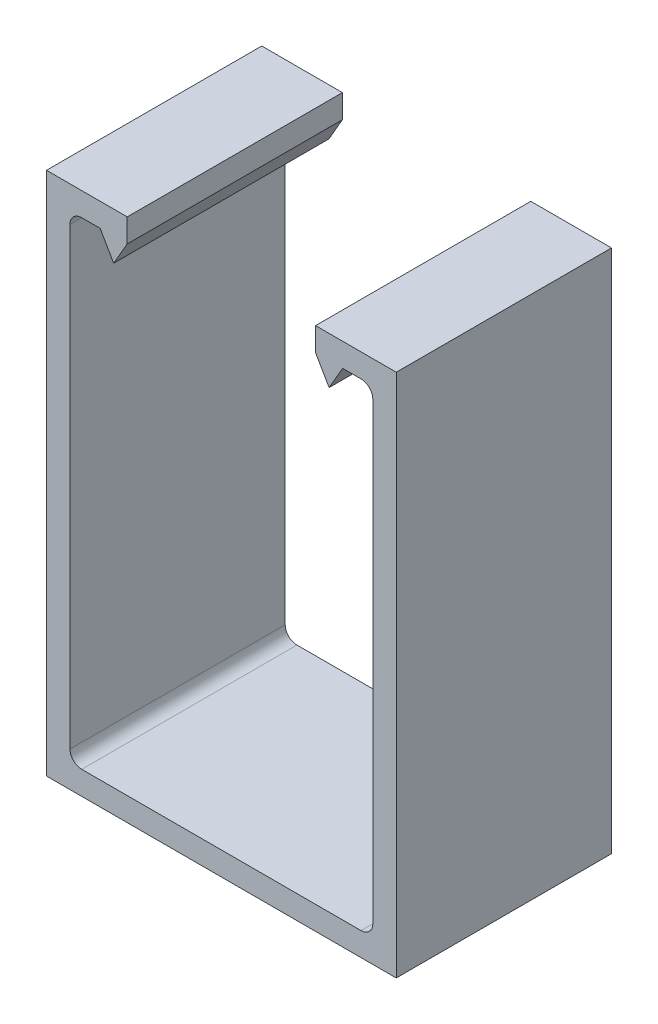
SolidWorks part; units mm, degrees
ref_plane "Plane1" through (0, 0, 0) normal (0, 0, 1) x (1, 0, 0)
ref_plane "Plane2" through (0, 0, 0) normal (0, 1, 0) x (1, 0, 0)
ref_plane "Plane3" through (0, 0, 0) normal (1, 0, 0) x (0, 0, -1)
sketch "Sketch1" plane through (0, 0, 0) normal (0, 0, 1) x (1, 0, 0)
  line L0 (-11.1125, 30.9562) -> (-20.6375, 30.9562)
  line L1 (-20.6375, 30.9562) -> (-20.6375, -30.9562)
  line L2 (-20.6375, -30.9562) -> (20.6375, -30.9562)
  line L3 (20.6375, -30.9562) -> (20.6375, 30.9563)
  line L4 (20.6375, 30.9563) -> (11.1125, 30.9563)
  line L5 (16.4846, 28.1877) -> (14.3094, 28.1877)
  line L6 (17.8689, -26.8033) -> (17.8689, 26.8034)
  line L7 (-16.4846, -28.1876) -> (16.4846, -28.1876)
  line L8 (-17.8689, 26.8033) -> (-17.8689, -26.8033)
  line L9 (-14.3094, 28.1876) -> (-16.4846, 28.1876)
  line L10 (14.3094, 28.1877) -> (12.711, 25.4191)
  line L11 (12.711, 25.4191) -> (11.1125, 28.1877)
  line L12 (11.1125, 28.1877) -> (11.1125, 30.9563)
  line L13 (-14.3094, 28.1876) -> (-12.711, 25.4191)
  line L14 (-12.711, 25.4191) -> (-11.1125, 28.1876)
  line L15 (-11.1125, 28.1876) -> (-11.1125, 30.9562)
  arc A0 (-17.8689, -26.8033) -> (-16.4846, -28.1876) centre (-16.4846, -26.8033) ccw
  arc A1 (-16.4846, 28.1876) -> (-17.8689, 26.8033) centre (-16.4846, 26.8033) ccw
  arc A2 (17.8689, 26.8034) -> (16.4846, 28.1877) centre (16.4846, 26.8034) ccw
  arc A3 (16.4846, -28.1876) -> (17.8689, -26.8033) centre (16.4846, -26.8033) ccw
  dimension "D5" = 1.3843
  dimension "Width" = 41.275
  dimension "Height" = 61.9125
  dimension "D8" = 20.6375
  dimension "D9" = 30.9562
  dimension "D10" = 22.225
  dimension "edge" = 9.525
  dimension "D13" = 1.5985
  dimension "D4" = 60
extrude "Base-Extrude" add sketch "Sketch1" along normal mid plane 25.4
equation "\"D8@Sketch1\" = \"Width@Sketch1\" / 2"
equation "\"D9@Sketch1\" = \"Height@Sketch1\" / 2"
equation "\"D10@Sketch1\" = \"Width@Sketch1\" - 2 * \"edge@Sketch1\""
equation "\"D5@Sketch1\" = \"gauge@Sketch1\" / 2"
equation "\"D13@Sketch1\" = \"gauge@Sketch1\" * .577350269"
